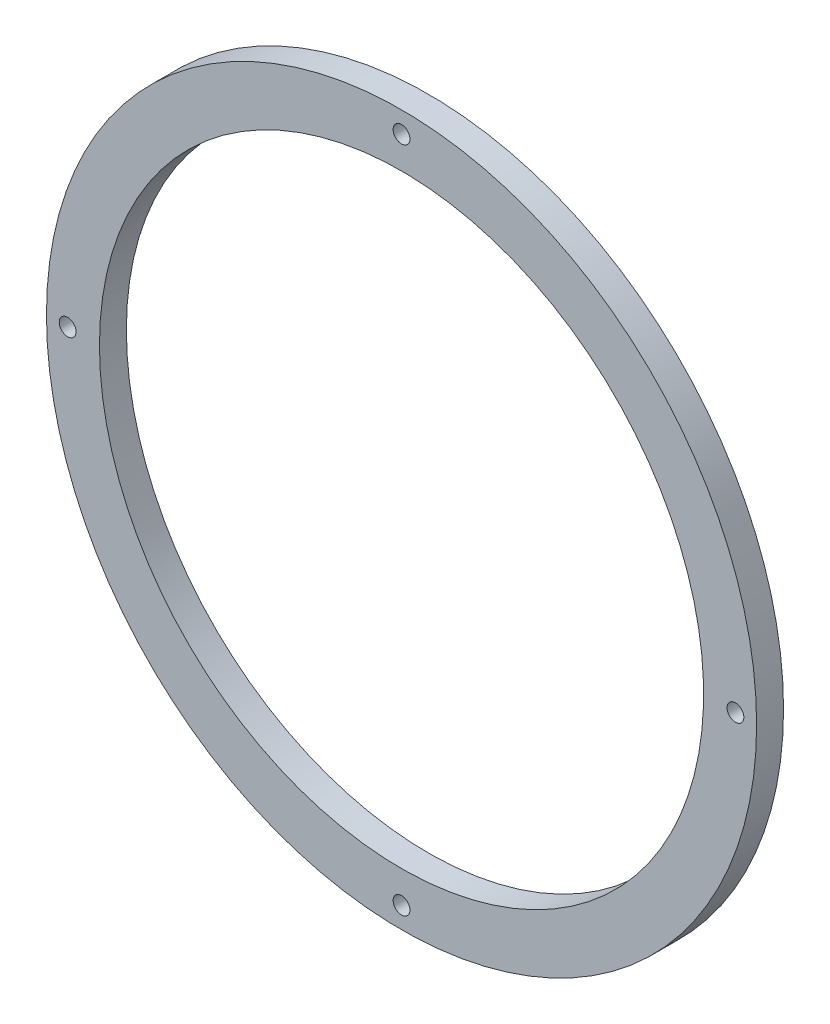
SolidWorks part; units mm, degrees
material "6061 Alloy"
ref_plane "Front Plane" through (0, 0, 0) normal (0, 0, 1) x (1, 0, 0)
ref_plane "Top Plane" through (0, 0, 0) normal (0, 1, 0) x (1, 0, 0)
ref_plane "Right Plane" through (0, 0, 0) normal (1, 0, 0) x (0, 0, -1)
sketch "Sketch1" plane through (0, 0, 0) normal (0, 0, 1) x (1, 0, 0)
  line L0 (0, 94.5) -> (0, 0) construction
  line L1 (0, 0) -> (-94.5, 0) construction
  line L2 (-94.5, 0) -> (0, 94.5) construction
  circle A0 centre (0, 0) radius 100.5
  circle A1 centre (0, 0) radius 85.5
  circle A2 centre (0, 94.5) radius 2.3812
  circle A3 centre (94.5, 0) radius 2.3813
  circle A4 centre (0, -94.5) radius 2.3812
  circle A5 centre (-94.5, 0) radius 2.3813
  point P16 (0, 0)
  dimension "D1" = 171
  dimension "D4" = 4.7625
  dimension "D3" = 94.5
  dimension "D6" = 94.5
  dimension "D2" = 15
  dimension "D5" = 4
extrude "Boss-Extrude1" add sketch "Sketch1" along normal blind 7.62
